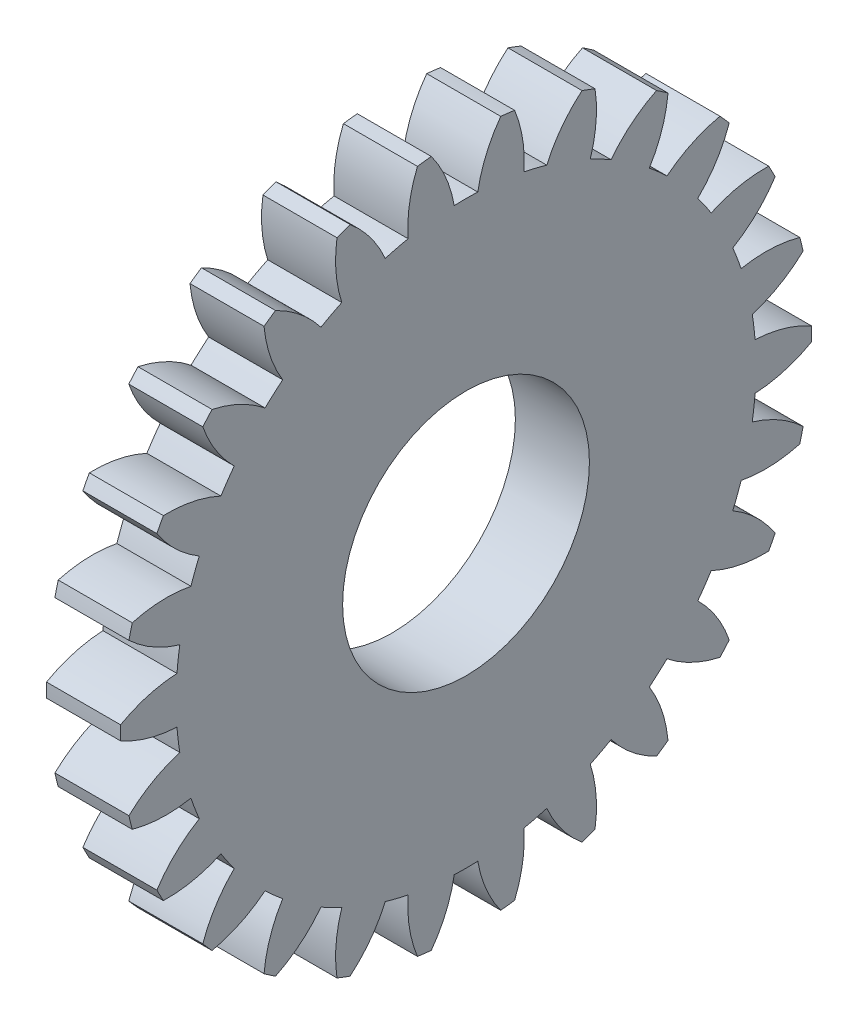
SolidWorks part; units mm, degrees
material "ﾎﾟﾘｵｷｼﾒﾁﾚﾝ(POM)ｱｾﾀｰﾙ共重合体"
ref_plane "Plane1" through (0, 0, 0) normal (0, 0, 1) x (1, 0, 0)
ref_plane "Plane2" through (0, 0, 0) normal (0, 1, 0) x (1, 0, 0)
ref_plane "Plane3" through (0, 0, 0) normal (1, 0, 0) x (0, 0, -1)
other "Configuration Table"
sketch "HoldingSke" plane through (0, 0, 0) normal (0, 1, 0) x (1, 0, 0)
  line L0 (0, 0) -> (0.8988, -0.4384)
  line L1 (-15, 0) -> (100, 0) construction
  line L2 (0, 0) -> (-2.1039, 2.3779)
  line L3 (0, 0) -> (-11.863, 4.5341)
  line L4 (0, 0) -> (7.762, 3.7858)
  line L5 (0, 0) -> (-46.8476, -17.4728)
  line L6 (0, 0) -> (-2.4869, -1.6779)
  line L7 (-2.1039, 2.3779) -> (8.6586, 51.2059)
  line L8 (-76.2, 54.61) -> (-75.2, 54.61)
  line L9 (-71.009, 38.7566) -> (-53.1078, 45.2721)
  line L10 (-76.2, 71.12) -> (104.1128, 71.12)
  line L11 (0, 0) -> (-3, 0)
  line L12 (-76.2, 101.6) -> (-76.162, 101.6)
  line L13 (24.9733, 27.94) -> (52.9518, 28.4284)
  line L14 (24.9733, 27.94) -> (24.9743, 27.94)
  line L15 (24.9733, 27.94) -> (100.4006, 29.5858)
  line L16 (-63.627, -1) -> (-12.827, -1)
  circle A0 centre (0, 0) radius 4
  circle A1 centre (0, 0) radius 11.749
  circle A2 centre (0, 0) radius 37.5
  circle A3 centre (0, 0) radius 4
  dimension "MHD" = 23.498
  dimension "Hub_dia" = 75
  dimension "Bore" = 8
  dimension "MBD" = 8
  dimension "Num_teeth" = 26
  dimension "Pitch" = 1
  dimension "Overall_len" = 50
  dimension "Show_teeth" = 26
  dimension "Thickness" = 3
  dimension "OAL" = 50.0001
  dimension "T_dim" = 1
  dimension "Ap" = 20
  dimension "H" = 19.05
  dimension "Pitch_radius" = 180.3128
  dimension "Width" = 3
  dimension "Backlash" = 0.038
  dimension "Addendum_fac" = 1
  dimension "Dedendum_fac" = 1.25
  dimension "Clearance_fac" = 0.25
  dimension "Dedendum_add" = 0.001
  dimension "Module" = 1
sketch "BasProSke" plane through (0, 0, 0) normal (0, 1, 0) x (1, 0, 0)
  line L0 (-10, 0) -> (60, 0) construction
  line L1 (0, 0) -> (0, 14)
  line L2 (0, 0) -> (3, 0)
  line L3 (3, 0) -> (3, 14)
  line L4 (3, 14) -> (0, 14)
  dimension "Thickness" = 3
  dimension "Diameter" = 28
revolve "Base-Revolve" add sketch "BasProSke" angle 360 about L0
sketch "TooCutSke" plane through (0, 0, 0) normal (1, 0, 0) x (0, 0, -1)
  line L1 (0, 0) -> (0, 107) construction
  line L2 (0, 0) -> (-0.8514, 12.9721) construction
  line L3 (0, 0) -> (-3.1292, 25.771) construction
  line L4 (-0.8514, 12.9721) -> (-1.5646, 12.8855) construction
  arc A0 (0.477, 11.7393) -> (-0.477, 11.7393) centre (0, 0) ccw
  arc A1 (1.4241, 13.9529) -> (-1.4241, 13.9529) centre (0, 0) ccw
  circle A2 centre (0, 0) radius 13 construction
  circle A3 centre (0, 0) radius 12.216 construction
  arc A4 (-0.477, 11.7393) -> (-1.4241, 13.9529) centre (-5.6014, 10.8561) ccw
  arc A5 (1.4241, 13.9529) -> (0.477, 11.7393) centre (5.6014, 10.8561) ccw
  dimension "Root_dia" = 23.498
  dimension "Overcut_dia" = 28.0508
  dimension "Pitch_dia" = 26
  dimension "Base_dia" = 24.432
  dimension "Flank_rad" = 5.2
  dimension "Half_ang" = 6.923
  dimension "Half_CT" = 0.7184
extrude "ToothCut" cut sketch "TooCutSke" along normal through all
fillet "Breaks" [suppressed] radius 0.02
fillet "RootFillets" [suppressed] radius 0.251
pattern_circular "TeethCuts" count 26 every 13.846 about axis through (-10, 0, 0) along (1, 0, 0) of "ToothCut", "RootFillets", "Breaks"
sketch "HubNeaOneSke" plane through (0, 0, 0) normal (-1, 0, 0) x (0, 0, 1)
  circle A0 centre (0, 0) radius 11.749
  dimension "Diameter" = 23.498
extrude "HubNearOne" [suppressed] add sketch "HubNeaOneSke" along normal blind 47.0001
sketch "HubNeaBotSke" plane through (0, 0, 0) normal (-1, 0, 0) x (0, 0, 1)
  circle A0 centre (0, 0) radius 11.749
  dimension "Diameter" = 23.498
extrude "HubNearBoth" [suppressed] add sketch "HubNeaBotSke" along normal blind 23.5
ref_plane "FarPln" through (3, 0, 0) normal (1, 0, 0) x (0, 0, -1)
sketch "HubFarSke" plane through (3, 0, 0) normal (1, 0, 0) x (0, 0, -1)
  circle A0 centre (0, 0) radius 11.749
  dimension "Diameter" = 23.498
extrude "HubFar" [suppressed] add sketch "HubFarSke" along normal blind 23.5
sketch "BorSke" plane through (0, 0, 0) normal (1, 0, 0) x (0, 0, -1)
  circle A0 centre (0, 0) radius 4
  dimension "Diameter" = 8
extrude "Bore" cut sketch "BorSke" along normal mid plane 100.0001
sketch "KeySke" plane through (0, 0, 0) normal (1, 0, 0) x (0, 0, -1)
  line L0 (-1, 0) -> (-1, 5)
  line L1 (-1, 5) -> (1, 5)
  line L2 (1, 5) -> (1, 0)
  line L3 (0, 0) -> (0, 34) construction
  line L4 (-1, 0) -> (1, 0)
  dimension "Offset" = 5
  dimension "Width" = 2
extrude "Keyway" [suppressed] cut sketch "KeySke" along normal mid plane 100.0001
pattern_circular "Keyway2" [suppressed] count 2 every 90 about axis through (-10, 0, 0) along (1, 0, 0)
sketch "ｽｹｯﾁ1" plane through (0, 0, 0) normal (-1, 0, 0) x (0, 0, 1)
  circle A0 centre (0, 0) radius 4
  dimension "D1" = 8
extrude "ﾎﾞｽ - 押し出し1" add sketch "ｽｹｯﾁ1" against normal up to surface (3 mm away) up to face at (3, 0, 4)
sketch "ｽｹｯﾁ2" plane through (0, 0, 0) normal (-1, 0, 0) x (0, 0, 1)
  circle A1 centre (0, 0) radius 5
  point P1 (0, 0)
  point P23 (0, 0)
  dimension "D1" = 10
extrude "ｶｯﾄ - 押し出し1" cut sketch "ｽｹｯﾁ2" against normal up to surface (3 mm away) up to face at (3, 0, 0)
equation "' \"Module@HoldingSke\" = 6.35"
equation "' \"Num_teeth@HoldingSke\" = 12"
equation "' \"Ap@HoldingSke\" =  20"
equation "' \"Ap@HoldingSke\" = 20"
equation "' \"Width@HoldingSke\" = 0.5 * 25.4"
equation "' \"Hub_dia@HoldingSke\"= 1 * 25.4"
equation "' \"Hub_dia@HoldingSke\" = 1 * 25.4"
equation "' \"Overall_len@HoldingSke\" = 1.0 * 25.4"
equation "' \"Bore@HoldingSke\" = 0.75 * 25.4"
equation "' \"T_dim@HoldingSke\" = 0.1 * 25.4"
equation "' \"Width@KeySke\" = 0.25 * 25.4"
equation "' \"Show_teeth@HoldingSke\" = 13"
equation "' \"Backlash@HoldingSke\" = 0.009 * 25.4"
equation "' \"Addendum_fac@HoldingSke\" = 1.0"
equation "' \"Dedendum_fac@HoldingSke\" = 1.25"
equation "' \"Dedendum_add@HoldingSke\" = 0.00005 * 25.4"
equation "' \"Clearance_fac@HoldingSke\" = 0.25"
equation "\"Pitch@HoldingSke\" = 1 / \"Module@HoldingSke\""
equation "\"Overcut_dia@TooCutSke\" = (\"Num_teeth@HoldingSke\" + 2 * \"Addendum_fac@HoldingSke\") / \"Pitch@HoldingSke\" + 0.002 * 25.4"
equation "\"Pitch_dia@TooCutSke\" = \"Num_teeth@HoldingSke\" / \"Pitch@HoldingSke\""
equation "\"Base_dia@TooCutSke\" = \"Num_teeth@HoldingSke\" / \"Pitch@HoldingSke\" * cos((\"Ap@HoldingSke\"  * 3.14159265 / 180))"
equation "\"Root_dia@TooCutSke\" = (\"Num_teeth@HoldingSke\" + 2) / \"Pitch@HoldingSke\" - 2 * (\"Addendum_fac@HoldingSke\" + \"Dedendum_fac@HoldingSke\") / \"Pitch@HoldingSke\" - \"Dedendum_add@HoldingSke\" * 2"
equation "\"Half_ang@TooCutSke\" = 180 / \"Num_teeth@HoldingSke\""
equation "\"Half_CT@TooCutSke\" = \"Num_teeth@HoldingSke\" / \"Pitch@HoldingSke\" * sin((3.14159265 / 2 / \"Num_teeth@HoldingSke\")) / 2 - 7 * \"Backlash@HoldingSke\" / 4"
equation "\"Flank_rad@TooCutSke\" = \"Num_teeth@HoldingSke\" / \"Pitch@HoldingSke\" / 5"
equation "\"Radius@RootFillets\" = \"Clearance_fac@HoldingSke\" / \"Pitch@HoldingSke\" + \"Dedendum_add@HoldingSke\""
equation "\"Break_rad@Breaks\" = 0.02 / \"Pitch@HoldingSke\""
equation "\"Thickness@HoldingSke\" = \"Width@HoldingSke\""
equation "\"OAL@HoldingSke\" = \"Thickness@HoldingSke\""
equation "\"MHD@HoldingSke\" = (\"Num_teeth@HoldingSke\" + 2) / \"Pitch@HoldingSke\" - 2 * (\"Addendum_fac@HoldingSke\" + \"Dedendum_fac@HoldingSke\")  / \"Pitch@HoldingSke\" - \"Dedendum_add@HoldingSke\" * 2"
equation "\"MBD@HoldingSke\" = (\"Num_teeth@HoldingSke\" + 2) / \"Pitch@HoldingSke\" - 2 * (\"Addendum_fac@HoldingSke\" + \"Dedendum_fac@HoldingSke\")  / \"Pitch@HoldingSke\" - \"Dedendum_add@HoldingSke\" * 2 - 0.002 * 25.4"
equation "\"MHD@HoldingSke\" = ((sgn( \"MHD@HoldingSke\" - \"Hub_dia@HoldingSke\" )-1)*( \"MHD@HoldingSke\" - \"Hub_dia@HoldingSke\" ))/-2+ \"Hub_dia@HoldingSke\""
equation "\"MBD@HoldingSke\" = ((sgn( \"MBD@HoldingSke\" - \"Bore@HoldingSke\" )-1)*( \"MBD@HoldingSke\" - \"Bore@HoldingSke\" ))/-2+ \"Bore@HoldingSke\""
equation "\"OAL@HoldingSke\" = ((sgn( \"OAL@HoldingSke\" - \"Overall_len@HoldingSke\" )+1)*( \"OAL@HoldingSke\" - \"Overall_len@HoldingSke\" ))/2 + \"Overall_len@HoldingSke\" + 0.000002 * 25.4"
equation "\"Num_teeth@TeethCuts\" = int( \"Show_teeth@HoldingSke\" ) + 1"
equation "\"Num_teeth@TeethCuts\" = ((sgn( \"Num_teeth@TeethCuts\" - \"Num_teeth@HoldingSke\" )-1)*( \"Num_teeth@TeethCuts\" - \"Num_teeth@HoldingSke\" ))/-2+ \"Num_teeth@HoldingSke\""
equation "\"Num_teeth@TeethCuts\" = ((sgn( \"Num_teeth@TeethCuts\" - 2.0)+1)*( \"Num_teeth@TeethCuts\" - 2.0))/2 +2.0"
equation "\"Angle@TeethCuts\" = 360.0 / \"Num_teeth@HoldingSke\""
equation "\"Diameter@BasProSke\" = (\"Num_teeth@HoldingSke\" + 2 * \"Addendum_fac@HoldingSke\") / \"Pitch@HoldingSke\""
equation "\"Thickness@BasProSke\"  = \"Thickness@HoldingSke\""
equation "' \"Fillet_rad@BasProSke\" =  \"Thickness@HoldingSke\" * 0.05"
equation "' \"Fillet_rad@BasProSke\" = \"Thickness@HoldingSke\" * 0.05"
equation "\"MHD@HoldingSke\" = ((sgn( \"MHD@HoldingSke\" - \"Root_dia@TooCutSke\" )-1)*( \"MHD@HoldingSke\" - \"Root_dia@TooCutSke\" ))/-2+ \"Root_dia@TooCutSke\""
equation "\"Diameter@HubNeaOneSke\" = \"MHD@HoldingSke\""
equation "\"Length@HubNearOne\" = \"OAL@HoldingSke\" - \"Thickness@BasProSke\""
equation "\"Diameter@HubNeaBotSke\" = \"MHD@HoldingSke\""
equation "\"Length@HubNearBoth\" = ( \"OAL@HoldingSke\" - \"Thickness@BasProSke\" ) / 2.0"
equation "\"Thickness@FarPln\" = \"Thickness@BasProSke\""
equation "\"Diameter@HubFarSke\" = \"MHD@HoldingSke\""
equation "\"Length@HubFar\" = ( \"OAL@HoldingSke\" - \"Thickness@BasProSke\" ) / 2.0"
equation "\"Diameter@BorSke\" = \"MBD@HoldingSke\""
equation "\"D1@Bore\" = \"OAL@HoldingSke\" * 2.0"
equation "\"D1@Keyway\" = \"OAL@HoldingSke\" * 2.0"
equation "\"Offset@KeySke\" = \"T_dim@HoldingSke\" + \"MBD@HoldingSke\" / 2.0"
